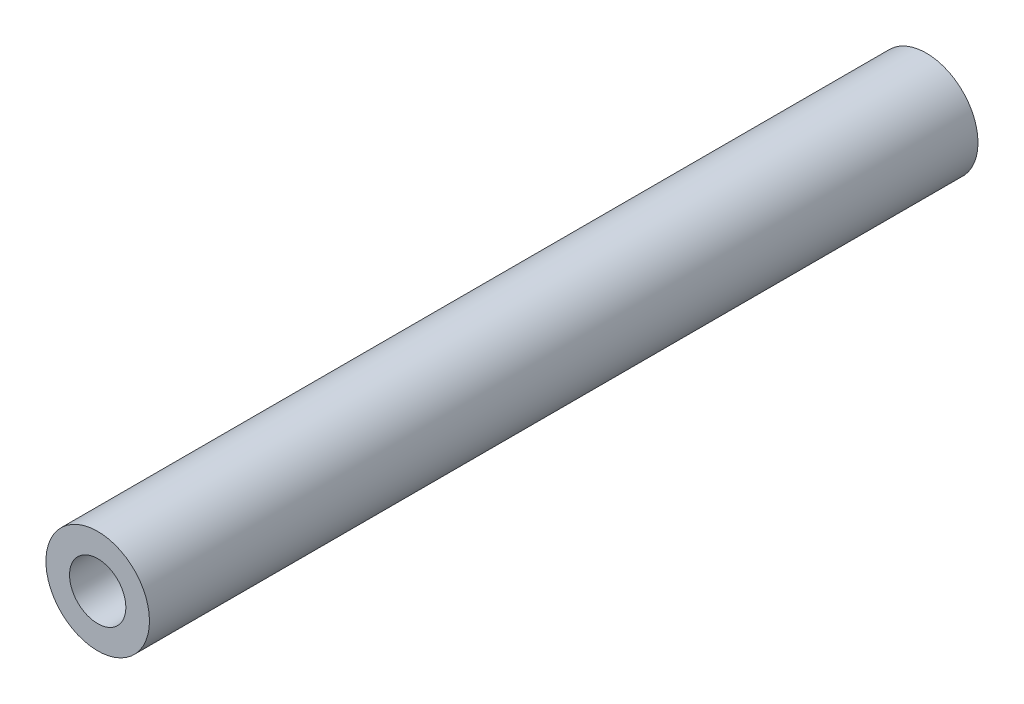
SolidWorks part; units mm, degrees
material "Alloy Steel"
ref_plane "Front Plane" through (0, 0, 0) normal (0, 0, 1) x (1, 0, 0)
ref_plane "Top Plane" through (0, 0, 0) normal (0, 1, 0) x (1, 0, 0)
ref_plane "Right Plane" through (0, 0, 0) normal (1, 0, 0) x (0, 0, -1)
sketch "Sketch1" plane through (0, 0, 0) normal (0, 0, 1) x (1, 0, 0)
  circle A0 centre (0, 0) radius 3.175
  dimension "D1" = 6.35
extrude "Boss-Extrude1" add sketch "Sketch1" along normal mid plane 50.8
hole_wizard "Tap Drill for #8-32 Tap1" positions "3DSketch1" profile "Sketch5" hole size "#8-32" standard "ANSI Inch"
sketch3d "3DSketch1"
  line L0 (0, 0, 25.4) -> (0, 0, -25.4) construction
  point P0 (0, 0, 25.4)
  point P4 (0, 0, -25.4)
sketch "Sketch5" plane through (0, 0, 25.4) normal (1, 0, 0) x (0, -1, 0)
  line L0 (0, 0) -> (0, 7.3878)
  line L1 (0, 7.3878) -> (1.7272, 6.35)
  line L2 (1.7272, 6.35) -> (1.7272, 0)
  line L5 (1.7272, 0) -> (0, 0)
  line L10 (0, 7.3878) -> (-1.7272, 6.35) construction
  line L11 (0, -6.35) -> (0, 107.95) construction
  dimension "Hole Dia." = 3.4544
  dimension "Hole Depth" = 6.35
  dimension "Drill Angle" = 118
